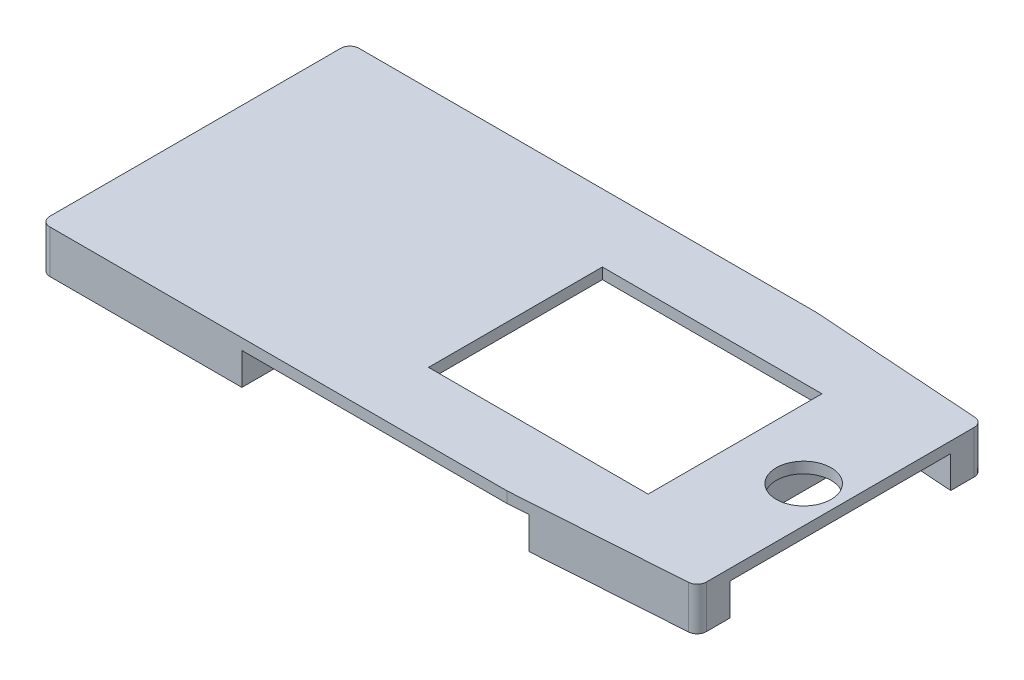
SolidWorks part; units mm, degrees
ref_plane "Front Plane" through (0, 0, 0) normal (0, 0, 1) x (1, 0, 0)
ref_plane "Top Plane" through (0, 0, 0) normal (0, 1, 0) x (1, 0, 0)
ref_plane "Right Plane" through (0, 0, 0) normal (1, 0, 0) x (0, 0, -1)
sketch "Sketch1" plane through (0, 0, 0) normal (0, 1, 0) x (1, 0, 0)
  line L0 (51, 33.8) -> (70.5, 32.475)
  line L1 (0, 0) -> (51, 0)
  line L2 (0, 0) -> (0, 33.8)
  line L3 (0, 33.8) -> (51, 33.8)
  line L5 (70.5, 32.475) -> (70.5, 1.325)
  line L6 (70.5, 1.325) -> (51, 0)
  line L8 (35, 26.4) -> (59, 26.4)
  line L9 (35, 26.4) -> (35, 7.4)
  line L10 (35, 7.4) -> (59, 7.4)
  line L11 (59, 26.4) -> (59, 7.4)
  circle A0 centre (66.5, 16.9) radius 3
  point P5 (70.5, 16.9)
  point P8 (0, 16.9)
  point P15 (59, 16.9)
  point P16 (0, 0)
  point P17 (0, 0)
  dimension "D6" = 6
  dimension "D1" = 33.8
  dimension "D2" = 51
  dimension "D3" = 70.5
  dimension "D4" = 31.15
  dimension "D5" = 1
  dimension "D7" = 35
  dimension "D8" = 59
  dimension "D9" = 19
extrude "Boss-Extrude1" add sketch "Sketch1" along normal blind 1.2
sketch "Sketch2" plane through (0, 0, 0) normal (0, -1, 0) x (1, 0, 0)
  line L0 (3.5, -3.5) -> (0, -3.5) construction
  line L1 (0, 0) -> (22, 0)
  line L2 (0, 0) -> (0, -3.5)
  line L3 (3.5, -3.5) -> (22, -3.5)
  line L4 (22, 0) -> (22, -3.5)
  line L5 (0, -33.8) -> (4.4051, -33.8)
  line L6 (0, -33.8) -> (0, -3.5)
  line L8 (3.5, -30.3) -> (3.5, -3.5)
  line L9 (4.4051, -33.8) -> (22, -33.8)
  line L11 (3.5, -30.3) -> (22, -30.3)
  line L12 (22, -33.8) -> (22, -30.3)
  line L13 (51, 0) -> (70.5, -1.325) construction
  line L14 (53.2367, -0.152) -> (70.5, -1.325)
  line L15 (70.5, -32.475) -> (51, -33.8) construction
  line L16 (70.5, -32.475) -> (53.2367, -33.648)
  line L17 (59, -26.4) -> (35, -26.4) construction
  line L18 (59, -7.4) -> (62.5, -7.4)
  line L19 (59, -7.4) -> (59, -26.4)
  line L20 (59, -26.4) -> (62.5, -26.4)
  line L21 (62.5, -7.4) -> (62.5, -26.4)
  line L22 (53.2367, -0.152) -> (53, -3.6359)
  line L23 (53, -3.6359) -> (70.5, -4.825)
  line L24 (70.5, -1.325) -> (70.5, -32.475) construction
  line L25 (70.5, -4.825) -> (70.5, -1.325)
  line L26 (53.2367, -33.648) -> (53, -30.1641)
  line L27 (53, -30.1641) -> (70.5, -28.975)
  line L28 (70.5, -28.975) -> (70.5, -32.475)
  dimension "D1" = 22
  dimension "D2" = 3.5
  dimension "D3" = 53
extrude "Boss-Extrude2" add sketch "Sketch2" along normal blind 3.5
fillet "Fillet1" radius 1 4 edges at (0, -1.15, -33.8) (70.5, -1.15, -32.475) (70.5, -1.15, -1.325) (0, -1.15, 0)
